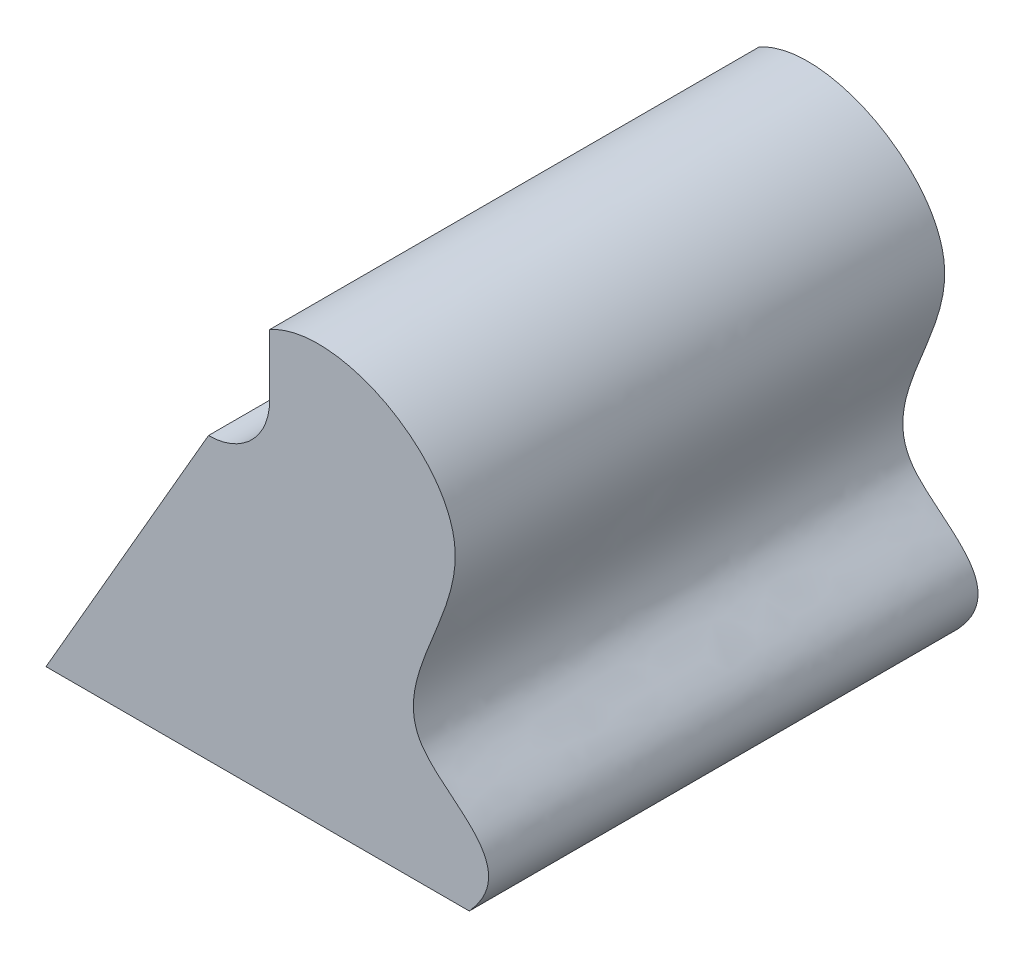
SolidWorks part; units mm, degrees
ref_plane "Plan de face" through (0, 0, 0) normal (0, 0, 1) x (1, 0, 0)
ref_plane "Plan de dessus" through (0, 0, 0) normal (0, 1, 0) x (1, 0, 0)
ref_plane "Plan de droite" through (0, 0, 0) normal (1, 0, 0) x (0, 0, -1)
sketch "Esquisse1" plane through (0, 0, 0) normal (0, 0, 1) x (1, 0, 0)
  line L0 (2.7578, 0) -> (37.3507, 0)
  line L1 (2.7578, 0) -> (16.0369, 23)
  line L2 (21.0369, 33) -> (21.0369, 28)
  line L3 (2.7578, 0) -> (14.3048, 20) construction
  line L4 (14.3048, 20) -> (-15.6952, 20) construction
  arc A0 (16.0369, 23) -> (21.0369, 28) centre (16.0369, 28) ccw
  spline S0 degree 3 poles (37.3507, 0) (41.9624, 5.0873) (26.6832, 9.1339) (43.2322, 27.2396) (26.6563, 36.1344) (21.0369, 33) knots 0 0 0 0 0.263848 0.594826 1 1 1 1
  point P16 (21.0369, 30.5)
  dimension "D4" = 5
  dimension "D1" = 5
  dimension "D2" = 5
  dimension "D3" = 3
extrude "Boss.-Extru.1" add sketch "Esquisse1" along normal mid plane 40
